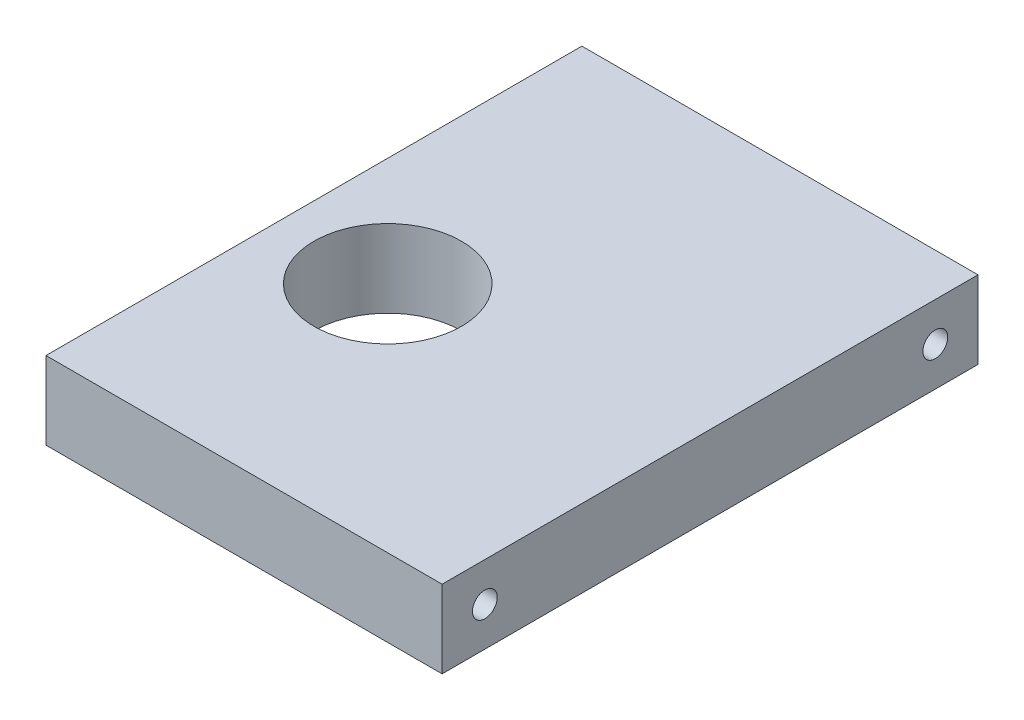
SolidWorks part; units mm, degrees
material "6061 合金"
ref_plane "前视基准面" through (0, 0, 0) normal (0, 0, 1) x (1, 0, 0)
ref_plane "上视基准面" through (0, 0, 0) normal (0, 1, 0) x (1, 0, 0)
ref_plane "右视基准面" through (0, 0, 0) normal (1, 0, 0) x (0, 0, -1)
sketch "草图1" plane through (0, 0, 0) normal (0, 1, 0) x (1, 0, 0)
  line L1 (-12.75, 17.25) -> (12.75, 17.25)
  line L2 (-12.75, 17.25) -> (-12.75, -17.25)
  line L3 (-12.75, -17.25) -> (12.75, -17.25)
  line L4 (12.75, 17.25) -> (12.75, -17.25)
  line L5 (-12.75, 17.25) -> (12.75, -17.25) construction
  line L6 (-12.75, -17.25) -> (12.75, 17.25) construction
  point P0 (0, 0)
  dimension "D1" = 25.5
  dimension "D2" = 34.5
extrude "凸台-拉伸1" add sketch "草图1" along normal blind 5
hole_wizard "M2x0.4 螺纹孔1" positions "3D草图1" profile "草图3" tap size "M2x0.4" standard "ANSI Metric"
sketch3d "3D草图1"
  line L1 (12.75, 0, 17.25) -> (12.75, 0, -17.25) construction
  line L3 (12.75, 5, 0) -> (12.75, 0, 0) construction
  line L4 (12.75, 5, 17.25) -> (12.75, 5, -17.25) construction
  point P0 (12.75, 2.5, -14.5)
  point P2 (12.75, 2.5, 14.5)
  dimension "D1" = 14.5
  dimension "D3" = 14.5
  dimension "D2" = 2.5
  dimension "D4" = 2.5
sketch "草图3" plane through (12.75, 2.5, -14.5) normal (0, 1, 0) x (0, 0, -1)
  line L0 (0, 0) -> (0, 5.6807)
  line L1 (0, 5.6807) -> (0.8, 5.2)
  line L2 (0.8, 5.2) -> (0.8, 0)
  line L5 (0.8, 0) -> (0, 0)
  line L10 (0, 5.6807) -> (-0.8, 5.2) construction
  line L11 (0, -6.35) -> (0, 107.95) construction
  dimension "螺纹孔钻头直径" = 1.6
  dimension "螺纹孔钻头深度" = 5.2
  dimension "导头角度" = 118
cosmetic thread "孔螺蚊线1"
cosmetic thread "孔螺蚊线2"
mirror "镜向1" about plane through (0, 0, 0) normal (1, 0, 0) of "M2x0.4 螺纹孔1"
sketch "草图4" plane through (0, 0, 0) normal (0, -1, 0) x (1, 0, 0)
  line L1 (-12.75, 0) -> (12.75, 0) construction
  line L3 (12.75, 17.25) -> (12.75, -17.25) construction
  line L4 (0, 17.25) -> (0, -17.25) construction
  line L5 (-12.75, 17.25) -> (12.75, 17.25) construction
  line L6 (12.75, -17.25) -> (-12.75, -17.25) construction
  line L8 (-12.75, -17.25) -> (-12.75, 17.25) construction
  circle A0 centre (-5.75, 2.25) radius 4.75
  dimension "D1" = 7
  dimension "D2" = 9.5
  dimension "D4" = 15
extrude "切除-拉伸1" cut sketch "草图4" against normal through all
